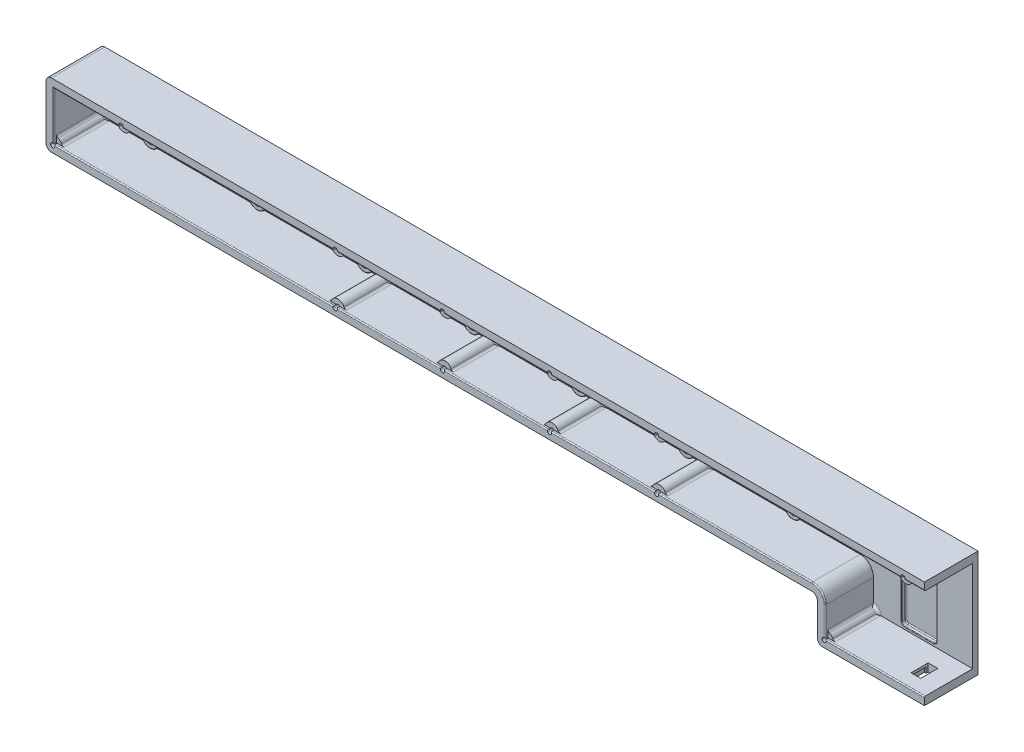
SolidWorks part; units mm, degrees
ref_plane "Front Plane" through (0, 0, 0) normal (0, 0, 1) x (1, 0, 0)
ref_plane "Top Plane" through (0, 0, 0) normal (0, 1, 0) x (1, 0, 0)
ref_plane "Right Plane" through (0, 0, 0) normal (1, 0, 0) x (0, 0, -1)
sketch "Sketch1" plane through (0, 0, 0) normal (0, 0, 1) x (1, 0, 0)
  line L0 (-50, 0) -> (0, 0) construction
  line L1 (-420, -70) -> (420, -70)
  line L2 (-420, -70) -> (-420, 70)
  line L3 (-420, 70) -> (420, 70)
  line L4 (420, -70) -> (420, 70)
  line L5 (-420, -70) -> (420, 70) construction
  line L6 (-420, 70) -> (420, -70) construction
  line L7 (0, 0) -> (50, 0) construction
  line L8 (250, 0) -> (350, 0) construction
  line L9 (333.7, -57.5) -> (333.7, 17.5)
  line L14 (334, -40) -> (350, 0) construction
  line L15 (334, 40) -> (334.4358, 38.9104) construction
  line L16 (336.5, 20.3) -> (363.5, 20.3)
  line L17 (366.3, -57.5) -> (366.3, 17.5)
  line L18 (336.5, -60.3) -> (363.5, -60.3)
  line L21 (365.5642, -38.9104) -> (366, -40) construction
  line L22 (365.5642, 38.9104) -> (366, 40) construction
  circle A0 centre (-350, 0) radius 4.15
  circle A1 centre (-250, 0) radius 4.15
  circle A2 centre (-150, 0) radius 4.15
  circle A3 centre (-50, 0) radius 4.15
  circle A4 centre (50, 0) radius 4.15
  circle A5 centre (150, 0) radius 4.15
  circle A6 centre (250, 0) radius 4.15
  circle A8 centre (350, 0) radius 4.15 [skipped]
  arc A13 (333.7, 17.5) -> (336.5, 20.3) centre (336.5, 17.5) cw
  arc A14 (363.5, 20.3) -> (366.3, 17.5) centre (363.5, 17.5) cw
  arc A15 (363.5, -60.3) -> (366.3, -57.5) centre (363.5, -57.5) ccw
  arc A16 (336.5, -60.3) -> (333.7, -57.5) centre (336.5, -57.5) cw
  point P0 (0, 0)
  dimension "D3" = 8.3
  dimension "D5" = 80
  dimension "D1" = 840
  dimension "D2" = 140
  dimension "D6" = 32
  dimension "D4" = 8
extrude "Boss-Extrude1" add sketch "Sketch1" along normal blind 5
sketch "Sketch2" plane through (0, 0, 5) normal (0, 0, 1) x (1, 0, 0)
  circle A0 centre (-350, 0) radius 8
  circle A1 centre (-350, 0) radius 4.15
extrude "Boss-Extrude3" add sketch "Sketch2" along normal blind 18
pattern_linear "LPattern1" count 7 spacing 100 along (1, 0, 0) of "Boss-Extrude3"
sketch "Sketch4" plane through (0, 0, 0) normal (0, 0, -1) x (-1, 0, 0)
  line L1 (-372.738, 24.1165) -> (-327.1271, 24.1165)
  line L2 (-372.738, 24.1165) -> (-372.738, -63.8212)
  line L3 (-372.738, -63.8212) -> (-327.1271, -63.8212)
  line L4 (-327.1271, 24.1165) -> (-327.1271, -63.8212)
extrude "Boss-Extrude4" add sketch "Sketch4" against normal blind 1
sketch "Sketch5" plane through (0, 70, 0) normal (0, 1, 0) x (1, 0, 0)
  line L4 (420, 0) -> (-420, 0)
  line L5 (-420, 0) -> (-420, -5)
  line L6 (-420, -5) -> (420, -5)
  line L7 (420, -5) -> (420, 0)
  line L8 (420, 0) -> (-420, 0)
  line L9 (-420, 0) -> (-420, -5)
  line L10 (-420, -5) -> (420, -5)
  line L11 (420, -5) -> (420, 0)
  dimension "D1" = 0
extrude "Cut-Extrude1" cut sketch "Sketch5" against normal blind 40
sketch "Sketch6" plane through (0, 0, 5) normal (0, 0, 1) x (1, 0, 0)
  line L0 (420, -70) -> (420, 30) construction
  line L1 (-420, -70) -> (300, -70)
  line L2 (-420, -70) -> (-420, -30)
  line L3 (-420, -30) -> (300, -30)
  line L4 (300, -70) -> (300, -30)
  dimension "D1" = 40
  dimension "D2" = 120
extrude "Cut-Extrude2" cut sketch "Sketch6" against normal through all
fillet "Fillet1" radius 5 4 edges at (300, -70, 2.5) (300, -30, 2.5) (-420, -30, 2.5) (-420, 30, 2.5)
fillet "Fillet2" radius 0.5 29 edges at (365.4799, -59.4799, 5) (350, -60.3, 5) (334.5201, -59.4799, 5) (333.7, -20, 5) (334.5201, 19.4799, 5) (350, 20.3, 5) (365.4799, 19.4799, 5) (-145.85, 0, 23) (-142, 0, 23) (-245.85, 0, 23) (-242, 0, 23) (366.3, -20, 5) (254.15, 0, 23) (258, 0, 23) (154.15, 0, 23) (158, 0, 23) (54.15, 0, 23) (58, 0, 23) (-45.85, 0, 23) (-42, 0, 23) (242, 0, 5) (142, 0, 5) (42, 0, 5) (-58, 0, 5) (-158, 0, 5) (-258, 0, 5) (-345.85, 0, 23) (-342, 0, 23) (-358, 0, 5)
fillet "Fillet3" radius 1 8 edges at (334.5201, 19.4799, 1) (333.7, -20, 1) (334.5201, -59.4799, 1) (350, -60.3, 1) (365.4799, -59.4799, 1) (366.3, -20, 1) (365.4799, 19.4799, 1) (350, 20.3, 1)
sketch "Sketch8" plane through (0, 0, 5) normal (0, 0, 1) x (1, 0, 0)
  line L0 (412.625, -62.625) -> (412.625, 22.625)
  line L1 (412.625, 22.625) -> (-412.625, 22.625)
  line L2 (-412.625, 22.625) -> (-412.625, -22.625)
  line L3 (-412.625, -22.625) -> (295, -22.625)
  line L4 (307.375, -35) -> (307.375, -62.625)
  line L5 (307.375, -62.625) -> (412.625, -62.625)
  line L6 (300, -35) -> (300, -65)
  line L7 (305, -70) -> (420, -70)
  line L8 (420, -70) -> (420, 30)
  line L9 (420, 30) -> (-415, 30)
  line L10 (-420, 25) -> (-420, -25)
  line L11 (-415, -30) -> (295, -30)
  line L12 (300, -35) -> (300, -65)
  line L13 (305, -70) -> (420, -70)
  line L14 (420, -70) -> (420, 30)
  line L15 (420, 30) -> (-415, 30)
  line L16 (-420, 25) -> (-420, -25)
  line L17 (-415, -30) -> (295, -30)
  arc A0 (-412.625, 22.625) -> (-412.625, 22.625) centre (-412.625, 22.625) ccw
  arc A1 (-412.625, -22.625) -> (-412.625, -22.625) centre (-412.625, -22.625) ccw
  arc A2 (307.375, -35) -> (295, -22.625) centre (295, -35) ccw
  arc A3 (307.375, -62.625) -> (307.375, -62.625) centre (307.375, -62.625) ccw
  arc A4 (300, -65) -> (305, -70) centre (305, -65) ccw
  arc A5 (-415, 30) -> (-420, 25) centre (-415, 25) ccw
  arc A6 (-420, -25) -> (-415, -30) centre (-415, -25) ccw
  arc A7 (300, -35) -> (295, -30) centre (295, -35) ccw
  arc A8 (300, -65) -> (305, -70) centre (305, -65) ccw
  arc A9 (-415, 30) -> (-420, 25) centre (-415, 25) ccw
  arc A10 (-420, -25) -> (-415, -30) centre (-415, -25) ccw
  arc A11 (300, -35) -> (295, -30) centre (295, -35) ccw
  dimension "D1" = 0
  dimension "D2" = 7.375
extrude "Boss-Extrude5" add sketch "Sketch8" along normal blind 45
ref_plane "Plane1" through (-140, 0, 0) normal (-1, 0, 0) x (0, 0, 1)
ref_plane "Plane2" through (140, 0, 0) normal (-1, 0, 0) x (0, 0, 1)
fillet "Fillet4" radius 1 3 edges at (307.375, -48.8125, 50) (303.7504, -26.2496, 50) (-58.8125, -22.625, 50)
sketch "Sketch10" plane through (0, 0, 50) normal (0, 0, 1) x (1, 0, 0)
  line L0 (412.625, -62.625) -> (412.625, 22.625) construction
  line L1 (412.625, 22.625) -> (420, 22.625)
  line L2 (412.625, 22.625) -> (412.625, -62.625)
  line L3 (412.625, -62.625) -> (420, -62.625)
  line L4 (420, 22.625) -> (420, -62.625)
  line L5 (412.625, -62.625) -> (412.625, 22.625) construction
  line L6 (420, -70) -> (420, 30) construction
extrude "Cut-Extrude3" cut sketch "Sketch10" against normal up to surface (45 mm away) up to face at (130.3304, -22.5267, 5)
fillet "Fillet5" radius 1 3 edges at (-412.625, -0.5, 50) (3.6875, 22.625, 50) (363.1875, -62.625, 50)
sketch "Sketch11" plane through (0, 0, 0) normal (0, 0, -1) x (-1, 0, 0)
  circle A0 centre (-250, 0) radius 4.15
  circle A1 centre (-150, 0) radius 4.15
  circle A2 centre (-50, 0) radius 4.15
  circle A3 centre (50, 0) radius 4.15
  circle A4 centre (150, 0) radius 4.15
  circle A5 centre (250, 0) radius 4.15
  circle A6 centre (350, 0) radius 4.15
  dimension "D1" = 7
extrude "Boss-Extrude6" add sketch "Sketch11" against normal blind 5
mirror "Mirror1" about plane through (420, -70, 5) normal (-1, 0, 0) of bodies 110
delete or keep bodies "Body-Delete/Keep 2" type delete bodies bodies 110
sketch "Sketch12" plane through (420, 0, 0) normal (-1, 0, 0) x (0, 0, 1)
  line L8 (50, 23.625) -> (50, 30)
  line L9 (50, 30) -> (0, 30)
  line L10 (0, 30) -> (0, -70)
  line L11 (0, -70) -> (50, -70)
  line L12 (50, -70) -> (50, -63.625)
  line L13 (49, -62.625) -> (5, -62.625)
  line L14 (5, -62.625) -> (5, 22.625)
  line L15 (5, 22.625) -> (49, 22.625)
  line L16 (50, 23.625) -> (50, 30)
  line L17 (50, 30) -> (0, 30)
  line L18 (0, 30) -> (0, -70)
  line L19 (0, -70) -> (50, -70)
  line L20 (50, -70) -> (50, -63.625)
  line L21 (49, -62.625) -> (5, -62.625)
  line L22 (5, -62.625) -> (5, 22.625)
  line L23 (5, 22.625) -> (49, 22.625)
  arc A2 (50, -63.625) -> (49, -62.625) centre (49, -63.625) ccw
  arc A3 (49, 22.625) -> (50, 23.625) centre (49, 23.625) ccw
  arc A4 (50, -63.625) -> (49, -62.625) centre (49, -63.625) ccw
  arc A5 (49, 22.625) -> (50, 23.625) centre (49, 23.625) ccw
  dimension "D1" = 0
extrude "Cut-Extrude4" cut sketch "Sketch12" against normal blind 20
sketch "Sketch13" plane through (0, -70, 0) normal (0, -1, 0) x (1, 0, 0)
  line L0 (535, 50) -> (440, 50) construction
  line L1 (455, 35) -> (467, 35)
  line L2 (455, 35) -> (455, 23)
  line L3 (455, 23) -> (467, 23)
  line L4 (467, 35) -> (467, 23)
  line L5 (440, 0) -> (440, 50) construction
  point P6 (455, 29)
  dimension "D1" = 12
  dimension "D2" = 12
  dimension "D3" = 15
  dimension "D4" = 15
extrude "Cut-Extrude5" cut sketch "Sketch13" against normal blind 5
sketch "Sketch14" plane through (0, -70, 0) normal (0, -1, 0) x (1, 0, 0)
  line L0 (467, 35) -> (455, 35) construction
  line L1 (456.5, 37) -> (465.5, 37)
  line L2 (456.5, 37) -> (456.5, 21)
  line L3 (456.5, 21) -> (465.5, 21)
  line L4 (465.5, 37) -> (465.5, 21)
  line L5 (455, 35) -> (455, 23) construction
  point P4 (461, 35)
  point P5 (455, 29)
  point P8 (461, 37)
  point P11 (456.5, 29)
  dimension "D1" = 9
  dimension "D2" = 16
extrude "Cut-Extrude6" cut sketch "Sketch14" against normal up to next
sketch "Sketch20" plane through (0, 0, 50) normal (0, 0, 1) x (1, 0, 0)
  line L0 (440, 30) -> (1255, 30) construction
  line L1 (1255, -30) -> (545, -30) construction
  line L2 (540, -35) -> (540, -65) construction
  line L3 (535, -70) -> (440, -70) construction
  line L5 (440, 23.625) -> (440, 30) construction
  line L12 (1255, 30) -> (440, 30)
  line L13 (440, 30) -> (440, 23.625)
  line L14 (440, 23.625) -> (1253.625, 23.625)
  line L15 (1253.625, 23.625) -> (1253.625, -23.625)
  line L16 (1253.625, -23.625) -> (545, -23.625)
  line L17 (533.625, -35) -> (533.625, -63.625)
  line L18 (533.625, -63.625) -> (440, -63.625)
  line L19 (440, -63.625) -> (440, -70)
  line L20 (440, -70) -> (535, -70)
  line L21 (540, -65) -> (540, -35)
  line L22 (545, -30) -> (1255, -30)
  line L23 (1260, -25) -> (1260, 25)
  line L35 (1260, -25) -> (1260, 25)
  circle A0 centre (790, 23.75) radius 1.95
  circle A1 centre (790, -23.75) radius 1.95
  circle A4 centre (460, 23.75) radius 1.95
  arc A5 (545, -23.625) -> (533.625, -35) centre (545, -35) ccw
  arc A6 (535, -70) -> (540, -65) centre (535, -65) ccw
  arc A7 (545, -30) -> (540, -35) centre (545, -35) ccw
  arc A8 (1255, -30) -> (1260, -25) centre (1255, -25) ccw
  arc A9 (1260, 25) -> (1255, 30) centre (1255, 25) ccw
  arc A11 (535, -70) -> (540, -65) centre (535, -65) ccw
  arc A12 (545, -30) -> (540, -35) centre (545, -35) ccw
  arc A13 (1255, -30) -> (1260, -25) centre (1255, -25) ccw
  arc A14 (1260, 25) -> (1255, 30) centre (1255, 25) ccw
  circle A15 centre (533.75, -63.75) radius 1.95
  circle A16 centre (690, 23.75) radius 1.95
  circle A17 centre (890, -23.75) radius 1.95
  circle A18 centre (990, 23.75) radius 1.95
  circle A19 centre (690, -23.75) radius 1.95
  circle A20 centre (890, 23.75) radius 1.95
  circle A21 centre (990, -23.75) radius 1.95
  circle A22 centre (1190, 23.75) radius 1.95
  circle A23 centre (1253.75, -23.75) radius 1.95
  point P13 (890, 0)
  point P28 (790, 0)
  point P44 (690, 0)
  point P46 (689.7552, 26.25)
  point P49 (990, 0)
  point P63 (1190, 0)
  dimension "D3" = 20
  dimension "D4" = 3.9
  dimension "D5" = 6.25
  dimension "D2" = 6.25
  dimension "D6" = 6.25
  dimension "D7" = 6.25
  dimension "D8" = 6.25
  dimension "D9" = 6.25
  dimension "D10" = 6.25
  dimension "D11" = 6.25
  dimension "D1" = 0
extrude "Cut-Extrude8" cut sketch "Sketch20" against normal blind 26 contours A4 | A15 | A16 | A19 | A20 | A17 | A18 | A21 | A22 | A23 | A1 | A0
ref_plane "Plane5" through (700, 0, 0) normal (-1, 0, 0) x (0, 0, 1)
ref_plane "Plane6" through (980, 0, 0) normal (-1, 0, 0) x (0, 0, 1)
ref_plane "Plane7" through (0, 0, 47.5) normal (0, 0, 1) x (1, 0, 0)
sketch "Sketch22" plane through (0, 0, 47.5) normal (0, 0, 1) x (1, 0, 0)
  circle A0 centre (460, 23.75) radius 1.95
  circle A1 centre (460, 23.75) radius 6.25
  circle A2 centre (690, 23.75) radius 1.95
  circle A3 centre (690, 23.75) radius 6.25
  circle A4 centre (790, 23.75) radius 1.95
  circle A5 centre (790, 23.75) radius 6.25
  circle A6 centre (890, 23.75) radius 1.95
  circle A7 centre (890, 23.75) radius 6.25
  circle A8 centre (990, 23.75) radius 1.95
  circle A9 centre (990, 23.75) radius 6.25
  circle A10 centre (1190, 23.75) radius 1.95
  circle A11 centre (1190, 23.75) radius 6.25
  circle A12 centre (1253.75, -23.75) radius 1.95
  circle A13 centre (1253.75, -23.75) radius 6.25
  circle A14 centre (990, -23.75) radius 1.95
  circle A16 centre (990, -23.75) radius 6.25
  circle A17 centre (890, -23.75) radius 1.95
  circle A18 centre (890, -23.75) radius 6.25
  circle A19 centre (790, -23.75) radius 1.95
  circle A20 centre (790, -23.75) radius 6.25
  circle A21 centre (690, -23.75) radius 1.95
  circle A22 centre (690, -23.75) radius 6.25
  circle A23 centre (533.75, -63.75) radius 1.95
  circle A24 centre (533.75, -63.75) radius 6.25
extrude "Boss-Extrude8" add sketch "Sketch22" against normal up to surface (42.5 mm away)
sketch "Sketch23" plane through (0, 0, 5) normal (0, 0, 1) x (1, 0, 0)
  line L1 (461.5928, 22.625) -> (458.4072, 22.625)
  line L2 (461.5928, 22.625) -> (458.4072, 22.625)
  line L3 (691.5928, 22.625) -> (688.4072, 22.625)
  line L4 (691.5928, 22.625) -> (688.4072, 22.625)
  line L5 (791.5928, 22.625) -> (788.4072, 22.625)
  line L6 (791.5928, 22.625) -> (788.4072, 22.625)
  line L7 (891.5928, 22.625) -> (888.4072, 22.625)
  line L8 (891.5928, 22.625) -> (888.4072, 22.625)
  line L9 (991.5928, 22.625) -> (988.4072, 22.625)
  line L10 (991.5928, 22.625) -> (988.4072, 22.625)
  line L11 (1191.5928, 22.625) -> (1188.4072, 22.625)
  line L12 (1191.5928, 22.625) -> (1188.4072, 22.625)
  line L13 (988.4072, -22.625) -> (991.5928, -22.625)
  line L14 (1252.1572, -22.625) -> (1252.625, -22.625)
  line L15 (1252.625, -22.625) -> (1252.625, -22.1572)
  line L16 (1252.1572, -22.625) -> (1252.625, -22.625)
  line L17 (1252.625, -22.625) -> (1252.625, -22.1572)
  line L18 (988.4072, -22.625) -> (991.5928, -22.625)
  line L19 (888.4072, -22.625) -> (891.5928, -22.625)
  line L20 (888.4072, -22.625) -> (891.5928, -22.625)
  line L21 (788.4072, -22.625) -> (791.5928, -22.625)
  line L22 (788.4072, -22.625) -> (791.5928, -22.625)
  line L23 (688.4072, -22.625) -> (691.5928, -22.625)
  line L24 (688.4072, -22.625) -> (691.5928, -22.625)
  line L26 (532.1572, -62.625) -> (532.625, -62.625)
  line L27 (532.625, -62.625) -> (532.625, -62.1572)
  line L28 (532.1572, -62.625) -> (532.625, -62.625)
  line L29 (532.625, -62.625) -> (532.625, -62.1572)
  arc A1 (458.4072, 22.625) -> (461.5928, 22.625) centre (460, 23.75) ccw
  arc A2 (458.4072, 22.625) -> (461.5928, 22.625) centre (460, 23.75) ccw
  arc A3 (688.4072, 22.625) -> (691.5928, 22.625) centre (690, 23.75) ccw
  arc A4 (688.4072, 22.625) -> (691.5928, 22.625) centre (690, 23.75) ccw
  arc A5 (788.4072, 22.625) -> (791.5928, 22.625) centre (790, 23.75) ccw
  arc A6 (788.4072, 22.625) -> (791.5928, 22.625) centre (790, 23.75) ccw
  arc A7 (888.4072, 22.625) -> (891.5928, 22.625) centre (890, 23.75) ccw
  arc A8 (888.4072, 22.625) -> (891.5928, 22.625) centre (890, 23.75) ccw
  arc A9 (988.4072, 22.625) -> (991.5928, 22.625) centre (990, 23.75) ccw
  arc A10 (988.4072, 22.625) -> (991.5928, 22.625) centre (990, 23.75) ccw
  arc A11 (1188.4072, 22.625) -> (1191.5928, 22.625) centre (1190, 23.75) ccw
  arc A12 (1188.4072, 22.625) -> (1191.5928, 22.625) centre (1190, 23.75) ccw
  arc A13 (1252.625, -22.1572) -> (1252.1572, -22.625) centre (1253.75, -23.75) ccw
  arc A14 (1252.625, -22.1572) -> (1252.1572, -22.625) centre (1253.75, -23.75) ccw
  arc A15 (991.5928, -22.625) -> (988.4072, -22.625) centre (990, -23.75) ccw
  arc A16 (991.5928, -22.625) -> (988.4072, -22.625) centre (990, -23.75) ccw
  arc A17 (891.5928, -22.625) -> (888.4072, -22.625) centre (890, -23.75) ccw
  arc A18 (891.5928, -22.625) -> (888.4072, -22.625) centre (890, -23.75) ccw
  arc A19 (791.5928, -22.625) -> (788.4072, -22.625) centre (790, -23.75) ccw
  arc A20 (791.5928, -22.625) -> (788.4072, -22.625) centre (790, -23.75) ccw
  arc A21 (691.5928, -22.625) -> (688.4072, -22.625) centre (690, -23.75) ccw
  arc A22 (691.5928, -22.625) -> (688.4072, -22.625) centre (690, -23.75) ccw
  arc A23 (532.625, -62.1572) -> (532.1572, -62.625) centre (533.75, -63.75) ccw
  arc A24 (532.625, -62.1572) -> (532.1572, -62.625) centre (533.75, -63.75) ccw
  dimension "D1" = 0
  dimension "D2" = 0
  dimension "D3" = 0
  dimension "D4" = 0
  dimension "D5" = 0
  dimension "D6" = 0
  dimension "D7" = 0
  dimension "D8" = 0
  dimension "D9" = 0
  dimension "D10" = 0
  dimension "D11" = 0
  dimension "D12" = 0
extrude "Boss-Extrude9" add sketch "Sketch23" along normal up to surface (19 mm away) up to face at (460, 24.1625, 24)
fillet "Fillet6" radius 2.5 36 edges at (1252.625, -17.6021, 26.25) (1247.6021, -22.625, 26.25) (1249.3306, -19.3306, 5) (983.8521, -22.625, 26.25) (996.1479, -22.625, 26.25) (990, -17.5, 5) (890, -17.5, 5) (883.8521, -22.625, 26.25) (896.1479, -22.625, 26.25) (783.8521, -22.625, 26.25) (796.1479, -22.625, 26.25) (790, -17.5, 5) (683.8521, -22.625, 26.25) (696.1479, -22.625, 26.25) (690, -17.5, 5) (532.625, -57.6021, 26.25) (529.3306, -59.3306, 5) (527.6021, -62.625, 26.25) (466.1479, 22.625, 26.25) (453.8521, 22.625, 26.25) (696.1479, 22.625, 26.25) (683.8521, 22.625, 26.25) (796.1479, 22.625, 26.25) (783.8521, 22.625, 26.25) (896.1479, 22.625, 26.25) (883.8521, 22.625, 26.25) (996.1479, 22.625, 26.25) (983.8521, 22.625, 26.25) (1196.1479, 22.625, 26.25) (1183.8521, 22.625, 26.25) (1190, 17.5, 5) (990, 17.5, 5) (890, 17.5, 5) (790, 17.5, 5) (690, 17.5, 5) (460, 17.5, 5)
mirror "Mirror2" about plane through (440, 23.625, 49) normal (-1, 0, 0)
delete or keep bodies "Body-Delete/Keep 3" type delete bodies bodies 120
